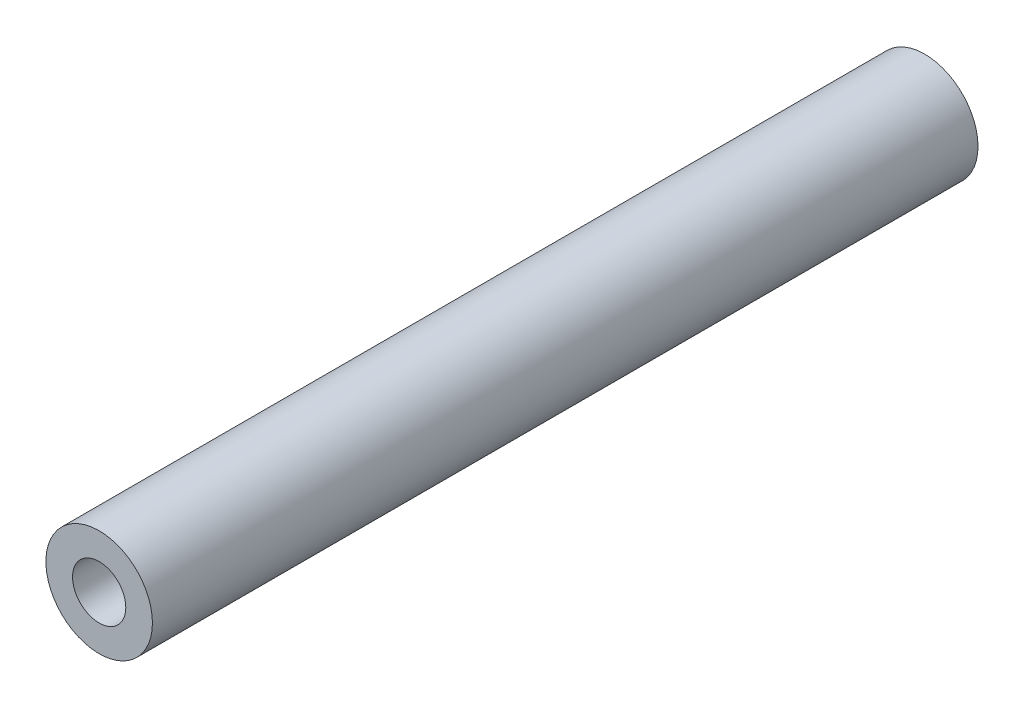
SolidWorks part; units mm, degrees
ref_plane "Front Plane" through (0, 0, 0) normal (0, 0, 1) x (1, 0, 0)
ref_plane "Top Plane" through (0, 0, 0) normal (0, 1, 0) x (1, 0, 0)
ref_plane "Right Plane" through (0, 0, 0) normal (1, 0, 0) x (0, 0, -1)
sketch "Sketch1" plane through (0, 0, 0) normal (0, 0, 1) x (1, 0, 0)
  circle A0 centre (0, 0) radius 3.175
  circle A1 centre (0, 0) radius 6.35
  dimension "D1" = 6.35
  dimension "D2" = 12.7
extrude "Boss-Extrude1" add sketch "Sketch1" along normal blind 98.425
